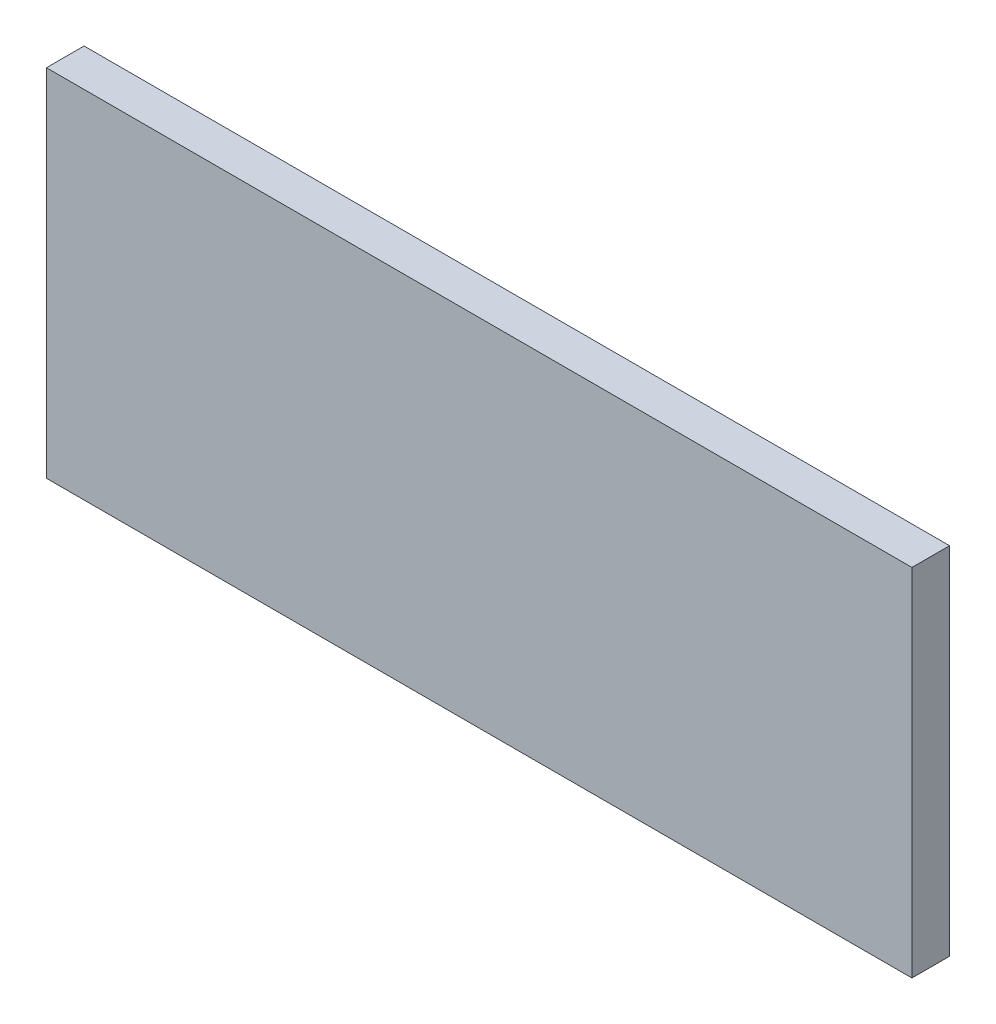
SolidWorks part; units mm, degrees
material "Pine"
ref_plane "Front Plane" through (0, 0, 0) normal (0, 0, 1) x (1, 0, 0)
ref_plane "Top Plane" through (0, 0, 0) normal (0, 1, 0) x (1, 0, 0)
ref_plane "Right Plane" through (0, 0, 0) normal (1, 0, 0) x (0, 0, -1)
sketch "Sketch1" plane through (0, 0, 0) normal (0, 0, 1) x (1, 0, 0)
  line L0 (-146.05, -60) -> (-146.05, 60)
  line L1 (-146.05, -60) -> (146.05, -60)
  line L2 (-146.05, 60) -> (146.05, 60)
  line L3 (146.05, -60) -> (146.05, 60)
  line L4 (-146.05, -60) -> (146.05, 60) construction
  line L5 (-146.05, 60) -> (146.05, -60) construction
  point P1 (0, 0)
  dimension "D1" = 120
  dimension "D2" = 292.1
extrude "Boss-Extrude1" add sketch "Sketch1" along normal blind 12.7
